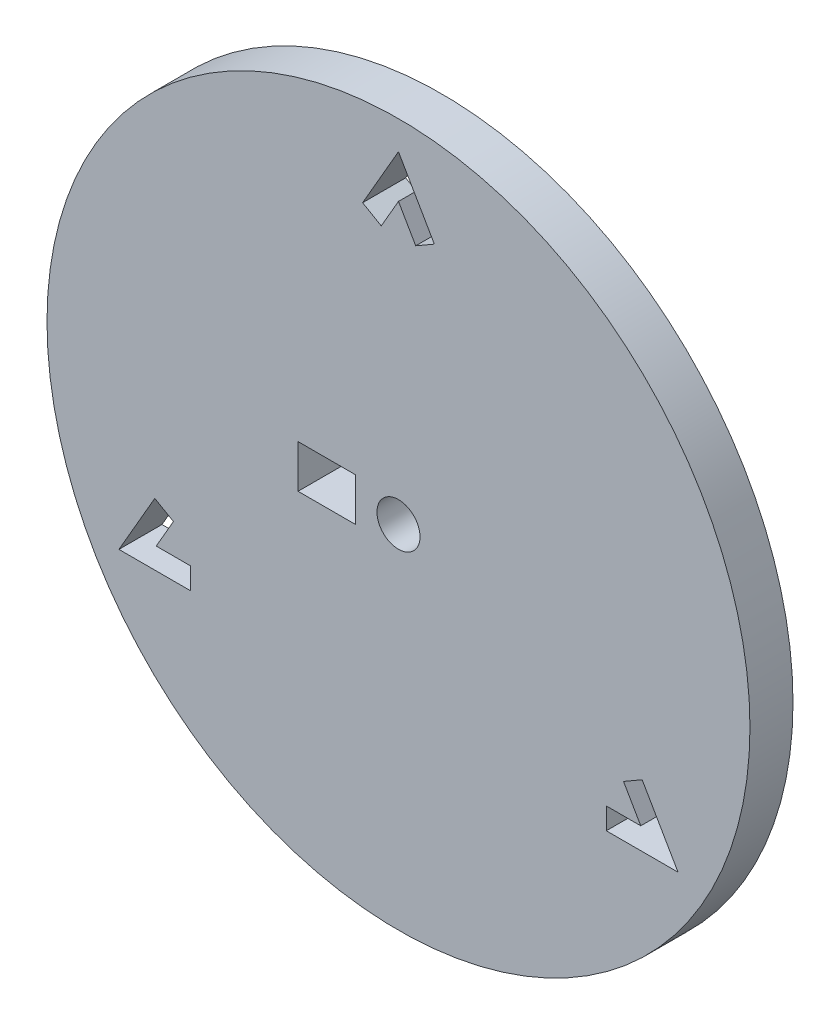
SolidWorks part; units mm, degrees
material "Acrílico (Impacto medio-alto)"
ref_plane "Alzado" through (0, 0, 0) normal (0, 0, 1) x (1, 0, 0)
ref_plane "Planta" through (0, 0, 0) normal (0, 1, 0) x (1, 0, 0)
ref_plane "Vista lateral" through (0, 0, 0) normal (1, 0, 0) x (0, 0, -1)
sketch "Croquis1" plane through (0, 0, 0) normal (0, 0, 1) x (1, 0, 0)
  line L0 (0, 45) -> (-5, 36.3397)
  line L1 (0, 45) -> (-38.9711, -22.5)
  line L2 (-38.9711, -22.5) -> (38.9711, -22.5)
  line L3 (38.9711, -22.5) -> (0, 45)
  line L4 (0, 45) -> (5, 36.3397)
  line L5 (5, 36.3397) -> (2.4019, 34.8397)
  line L6 (-5, 36.3397) -> (-2.4019, 34.8397)
  line L7 (-2.4019, 34.8397) -> (0, 39)
  line L8 (2.4019, 34.8397) -> (0, 39)
  line L9 (0, 39) -> (0, 45)
  line L10 (-38.9711, -22.5) -> (-28.9711, -22.5)
  line L11 (-28.9711, -22.5) -> (-28.9711, -19.5)
  line L12 (-38.9711, -22.5) -> (-33.9711, -13.8397)
  line L13 (-33.9711, -13.8397) -> (-31.3731, -15.3397)
  line L14 (-31.3731, -15.3397) -> (-33.775, -19.5)
  line L15 (-28.9711, -19.5) -> (-33.775, -19.5)
  line L16 (38.9711, -22.5) -> (33.9711, -13.8397)
  line L17 (33.9711, -13.8397) -> (31.3731, -15.3397)
  line L18 (38.9711, -22.5) -> (28.9711, -22.5)
  line L19 (28.9711, -22.5) -> (28.9711, -19.5)
  line L20 (31.3731, -15.3397) -> (33.775, -19.5)
  line L21 (28.9711, -19.5) -> (33.775, -19.5)
  circle A0 centre (0, 0) radius 49
  circle A1 centre (0, 0) radius 22.5 construction
  dimension "D1" = 98
  dimension "D2" = 45
  dimension "D3" = 10
  dimension "D4" = 3
  dimension "D5" = 3
  dimension "D6" = 10
  dimension "D7" = 10
  dimension "D8" = 3
  dimension "D9" = 3
  dimension "D10" = 10
  dimension "D11" = 10
  dimension "D12" = 3
  dimension "D13" = 3
extrude "Saliente-Extruir1" add sketch "Croquis1" along normal blind 6 contours A0 L3 L2 L1 L0 | L19 L21 L20 L17 L3 L5 L8 L7 L6 L1 L13 L14 L15 L11 L2
sketch "Croquis2" plane through (0, 0, 6) normal (0, 0, 1) x (1, 0, 0)
  line L1 (-14, 3) -> (-6, 3)
  line L2 (-14, 3) -> (-14, -3)
  line L3 (-14, -3) -> (-6, -3)
  line L4 (-6, 3) -> (-6, -3)
  line L5 (-14, 3) -> (-6, -3) construction
  line L6 (-14, -3) -> (-6, 3) construction
  circle A0 centre (0, 0) radius 3
  circle A1 centre (0, 0) radius 10
  point P4 (-10, 0)
  dimension "D1" = 6
  dimension "D2" = 20
  dimension "D3" = 6
  dimension "D4" = 8
extrude "Cortar-Extruir1" cut sketch "Croquis2" against normal blind 10 contours A1 L1 L2 L3 | L1 A1 L3 L4 | A0
